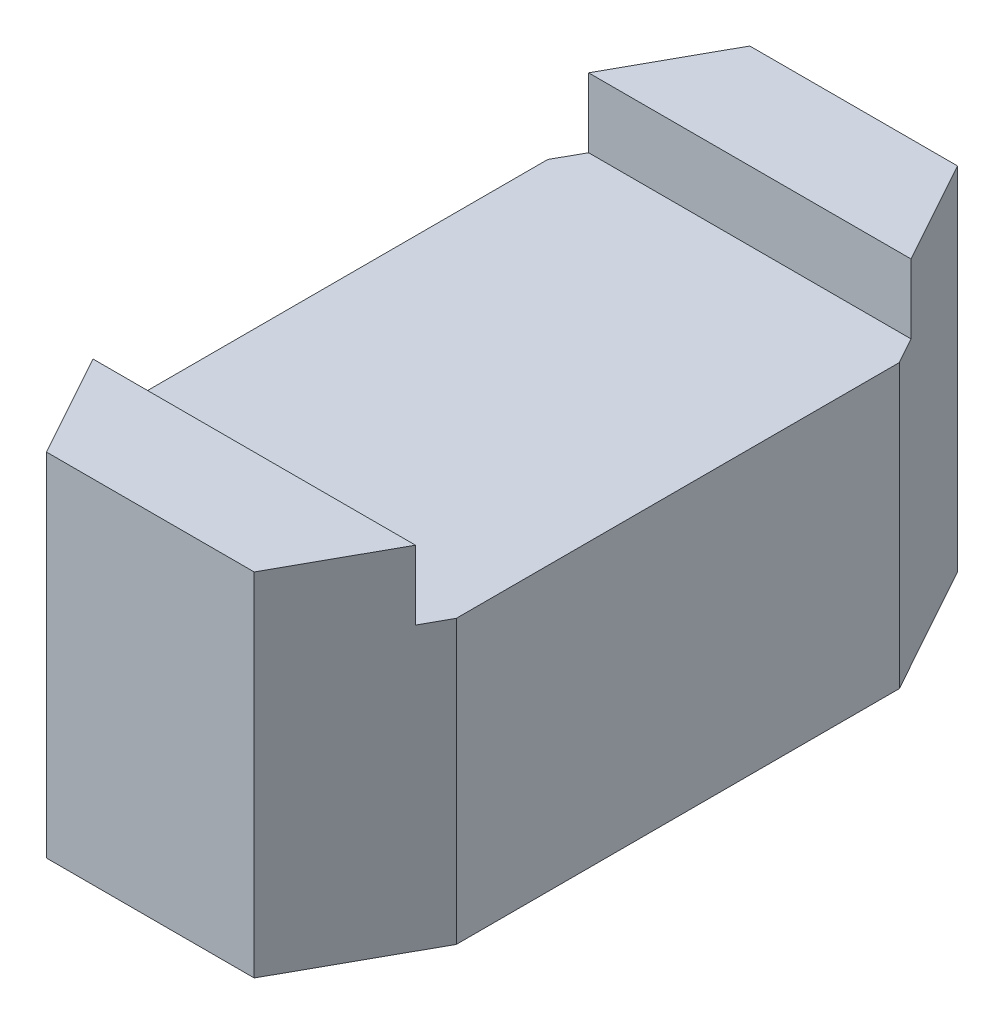
SolidWorks part; units mm, degrees
ref_plane "Спереди" through (0, 0, 0) normal (0, 0, 1) x (1, 0, 0)
ref_plane "Сверху" through (0, 0, 0) normal (0, 1, 0) x (1, 0, 0)
ref_plane "Справа" through (0, 0, 0) normal (1, 0, 0) x (0, 0, -1)
sketch "Эскиз1" plane through (0, 0, 0) normal (0, 1, 0) x (1, 0, 0)
  line L0 (-0.75, 2.54) -> (-1.27, 1.6)
  line L1 (-0.75, 2.54) -> (0.75, 2.54)
  line L2 (-1.27, 1.6) -> (-1.27, -1.6)
  line L3 (-0.75, -2.54) -> (0.75, -2.54)
  line L4 (1.27, 1.6) -> (1.27, -1.6)
  line L5 (0.75, 2.54) -> (1.27, 1.6)
  line L6 (1.27, -1.6) -> (0.75, -2.54)
  line L7 (-1.27, -1.6) -> (-0.75, -2.54)
  line L8 (-1.27, 1.27) -> (1.27, 1.27) construction
  point P4 (1.27, 0)
  point P6 (0, 2.54)
  dimension "D1" = 2.54
  dimension "D2" = 5.08
  dimension "D3" = 3.2
  dimension "D4" = 1.5
  dimension "D5" = 1.27
extrude "Бобышка-Вытянуть1" add sketch "Эскиз1" along normal blind 2.54
sketch "Эскиз2" plane through (0, 2.54, 0) normal (0, 1, 0) x (1, 0, 0)
  line L0 (-1.27, 1.6) -> (-1.27, -1.6) construction
  line L1 (-1.27, 1.79) -> (1.27, 1.79)
  line L2 (-1.27, 1.79) -> (-1.27, -1.79)
  line L3 (-1.27, -1.79) -> (1.27, -1.79)
  line L4 (1.27, 1.79) -> (1.27, -1.79)
  line L5 (1.27, -1.6) -> (1.27, 1.6) construction
  point P8 (-1.27, 0)
  dimension "D1" = 3.58
extrude "Вырез-Вытянуть1" cut sketch "Эскиз2" against normal blind 0.5
ref_plane "Плоскость1" through (0, 0, -1.27) normal (0, 0, -1) x (1, 0, 0)
